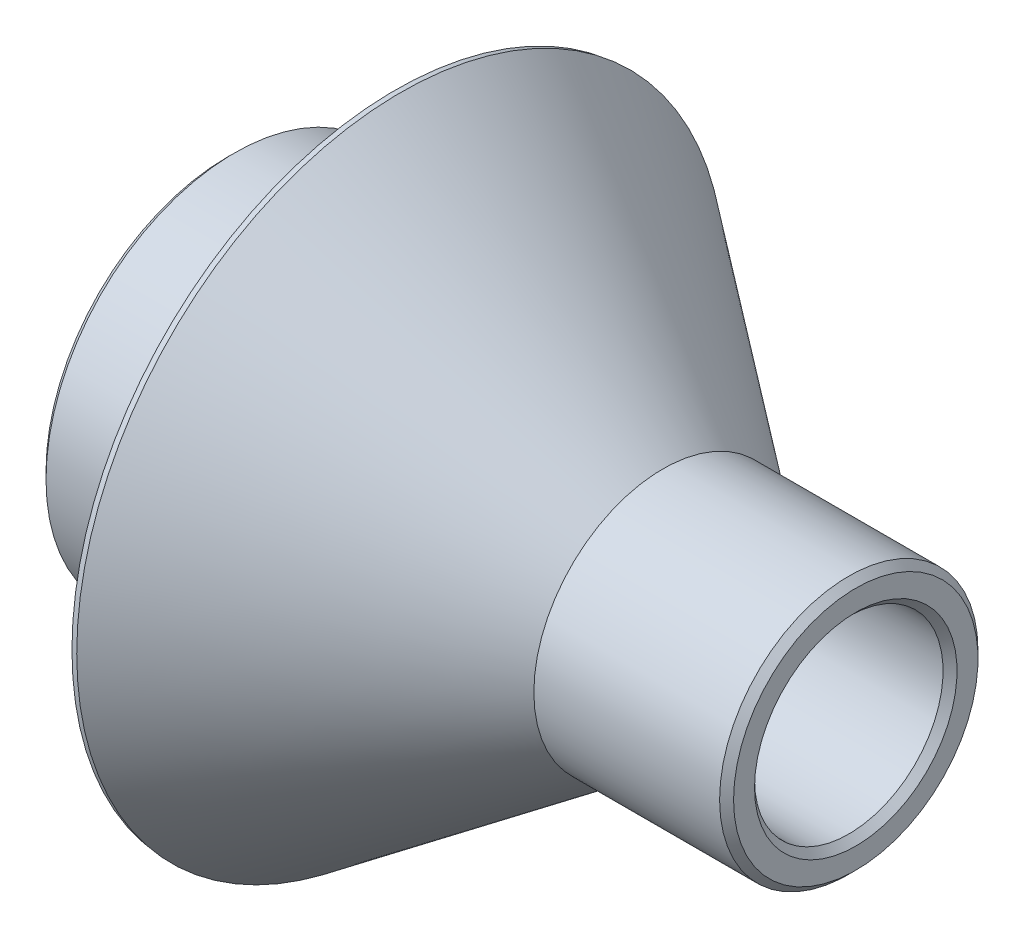
SolidWorks part; units mm, degrees
ref_plane "Front Plane" through (0, 0, 0) normal (0, 0, 1) x (1, 0, 0)
ref_plane "Top Plane" through (0, 0, 0) normal (0, 1, 0) x (1, 0, 0)
ref_plane "Right Plane" through (0, 0, 0) normal (1, 0, 0) x (0, 0, -1)
sketch "Sketch1" plane through (0, 0, 0) normal (0, 0, 1) x (1, 0, 0)
  line L0 (0, 0) -> (6.096, 0)
  line L1 (6.096, 0) -> (6.096, 6.858)
  line L2 (6.096, 6.858) -> (6.096, 11.938)
  line L3 (0, 0) -> (6.096, 0)
  line L4 (0, 0) -> (0, 6.858)
  line L5 (0, 6.858) -> (6.096, 6.858)
  line L6 (6.096, 0) -> (6.096, 6.858)
  line L7 (15.8369, 0) -> (15.8369, 4.699)
  line L8 (22.8473, 0) -> (22.8473, 4.699)
  line L9 (22.8473, 4.699) -> (15.8369, 4.699)
  line L10 (15.8369, 4.699) -> (6.096, 11.938)
  line L11 (6.096, 0) -> (18.6182, 0)
  line L12 (17.1069, 0) -> (20.1295, 0)
  line L13 (15.8369, 0) -> (21.3995, 0)
  line L14 (21.3995, 0) -> (22.8473, 0)
  point P13 (18.6182, 0)
  point P15 (18.6182, 0)
  dimension "D1" = 6.096
  dimension "D2" = 6.858
  dimension "D3" = 5.08
  dimension "D5" = 4.699
  dimension "D6" = 12.5222
  dimension "D7" = 3.0226
  dimension "D8" = 5.5626
  dimension "D9" = 1.4478
revolve "Revolve1" add sketch "Sketch1" angle 360 about L11
sketch "Sketch2" plane through (22.8473, 0, 0) normal (1, 0, 0) x (0, 0, -1)
  circle A0 centre (0, 0) radius 3.429
  dimension "D1" = 6.858
extrude "Cut-Extrude1" cut sketch "Sketch2" against normal through all
chamfer "Chamfer1" distance 0.254 angle 45 5 edges at (0, 0, -3.429) (0, 0, 6.858) (6.096, 0, 11.938) (22.8473, 0, -3.429) (22.8473, 0, 4.699)
